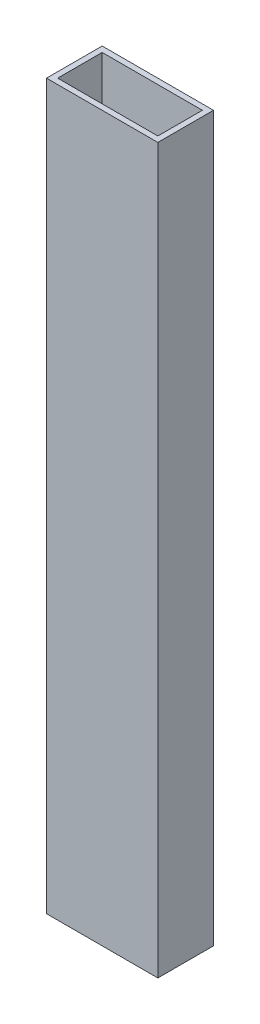
SolidWorks part; units mm, degrees
ref_plane "Front Plane" through (0, 0, 0) normal (0, 0, 1) x (1, 0, 0)
ref_plane "Top Plane" through (0, 0, 0) normal (0, 1, 0) x (1, 0, 0)
ref_plane "Right Plane" through (0, 0, 0) normal (1, 0, 0) x (0, 0, -1)
sketch "Sketch1" plane through (0, 0, 0) normal (0, 1, 0) x (1, 0, 0)
  line L1 (-50.8, 25.4) -> (0, 25.4)
  line L2 (-50.8, 25.4) -> (-50.8, 0)
  line L3 (-50.8, 0) -> (0, 0)
  line L4 (0, 25.4) -> (0, 0)
  dimension "D1" = 25.4
  dimension "D2" = 50.8
extrude "Extrude-Thin1" add sketch "Sketch1" along normal blind 330.2 thin
